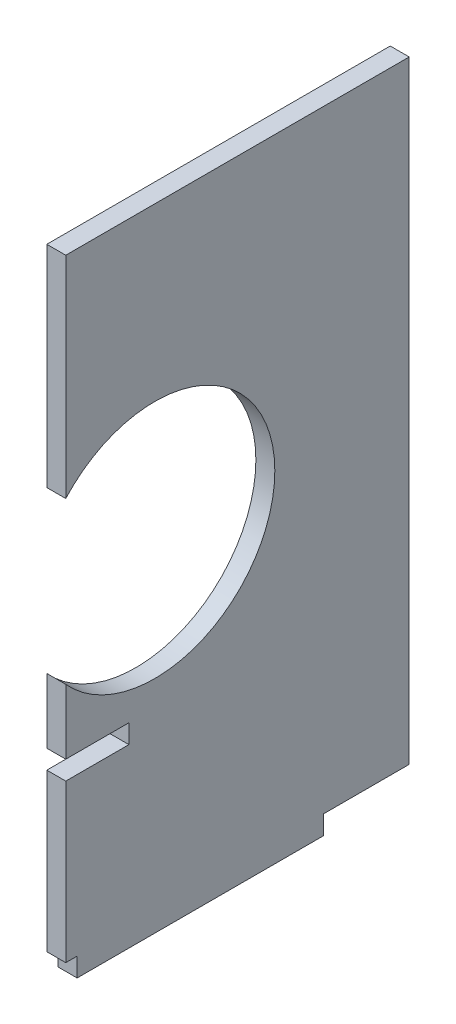
SolidWorks part; units mm, degrees
ref_plane "Plan de face" through (0, 0, 0) normal (0, 0, 1) x (1, 0, 0)
ref_plane "Plan de dessus" through (0, 0, 0) normal (0, 1, 0) x (1, 0, 0)
ref_plane "Plan de droite" through (0, 0, 0) normal (1, 0, 0) x (0, 0, -1)
ref_plane "Plan1" through (3, 0, 0) normal (1, 0, 0) x (0, 0, -1)
sketch "Esquisse1" plane through (3, 0, 0) normal (1, 0, 0) x (0, 0, -1)
  line L0 (-5.1057, -9.4265) -> (-59.4757, -9.4265)
  line L1 (-59.4757, -9.4265) -> (-59.4757, -42.7888)
  line L2 (-59.4757, -68.2643) -> (-59.4757, -78.5265)
  line L3 (-59.4757, -78.5265) -> (-49.4757, -78.5265)
  line L4 (-49.4757, -78.5265) -> (-49.4757, -81.5265)
  line L5 (-49.4757, -81.5265) -> (-59.4757, -81.5265)
  line L6 (-59.4757, -81.5265) -> (-59.4757, -106.4265)
  line L7 (-59.4757, -106.4265) -> (-57.6757, -106.4265)
  line L8 (-57.6757, -106.4265) -> (-57.6757, -109.4265)
  line L9 (-57.6757, -109.4265) -> (-18.6757, -109.4265)
  line L10 (-18.6757, -109.4265) -> (-18.6757, -106.4265)
  line L11 (-18.6757, -106.4265) -> (-5.1057, -106.4265)
  line L12 (-5.1057, -106.4265) -> (-5.1057, -9.4265)
  arc A0 (-59.4757, -42.7888) -> (-59.4757, -68.2643) centre (-45.3778, -55.5265) cw
  dimension "D1" = 19
  dimension "D2" = 39
extrude "Boss.-Extru.1" add sketch "Esquisse1" against normal blind 3
